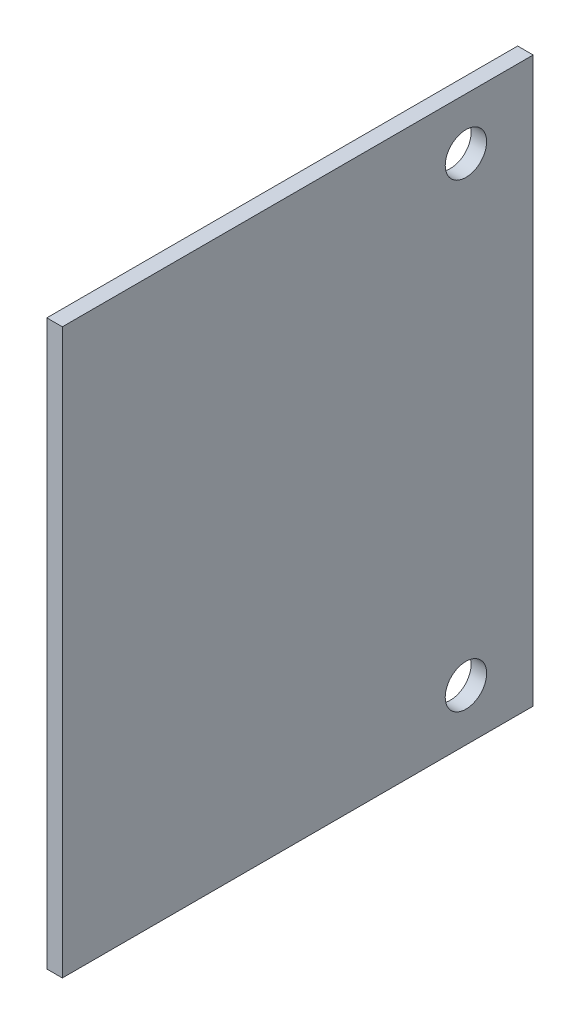
SolidWorks part; units mm, degrees
ref_plane "Front Plane" through (0, 0, 0) normal (0, 0, 1) x (1, 0, 0)
ref_plane "Top Plane" through (0, 0, 0) normal (0, 1, 0) x (1, 0, 0)
ref_plane "Right Plane" through (0, 0, 0) normal (1, 0, 0) x (0, 0, -1)
sketch "Sketch1" plane through (0, 0, 0) normal (0, 1, 0) x (1, 0, 0)
  line L0 (-476.25, 298.45) -> (-457.2, 298.45)
  line L1 (-476.25, 298.45) -> (476.25, 298.45) construction
  line L2 (-457.2, 298.45) -> (-457.2, -279.4)
  line L3 (-438.15, -279.4) -> (-476.25, -279.4) construction
  line L4 (-457.2, -279.4) -> (-476.25, -279.4)
  line L5 (-476.25, -279.4) -> (-476.25, 298.45)
  dimension "D1" = 19.05
extrude "Boss-Extrude1" add sketch "Sketch1" along normal offset from surface (692.15 mm away) 19.05
sketch "Sketch2" plane through (-476.25, 0, 0) normal (-1, 0, 0) x (0, 0, 1)
  line L0 (-279.4, 692.15) -> (-279.4, 0) construction
  line L1 (-298.45, 692.15) -> (279.4, 692.15) construction
  line L2 (-298.45, 0) -> (279.4, 0) construction
  line L3 (-279.4, 692.15) -> (-279.4, 0) construction
  line L4 (-215.9, 692.15) -> (-215.9, 624.1249) construction
  circle A0 centre (-215.9, 628.65) radius 25.4
  circle A1 centre (-215.9, 63.5) radius 25.4
  dimension "D1" = 50.8
  dimension "D4" = 50.8
  dimension "D2" = 63.5
  dimension "D3" = 63.5
  dimension "D5" = 63.5
extrude "Cut-Extrude1" cut sketch "Sketch2" against normal through all
equation "\"inner_height\"= 30in"
